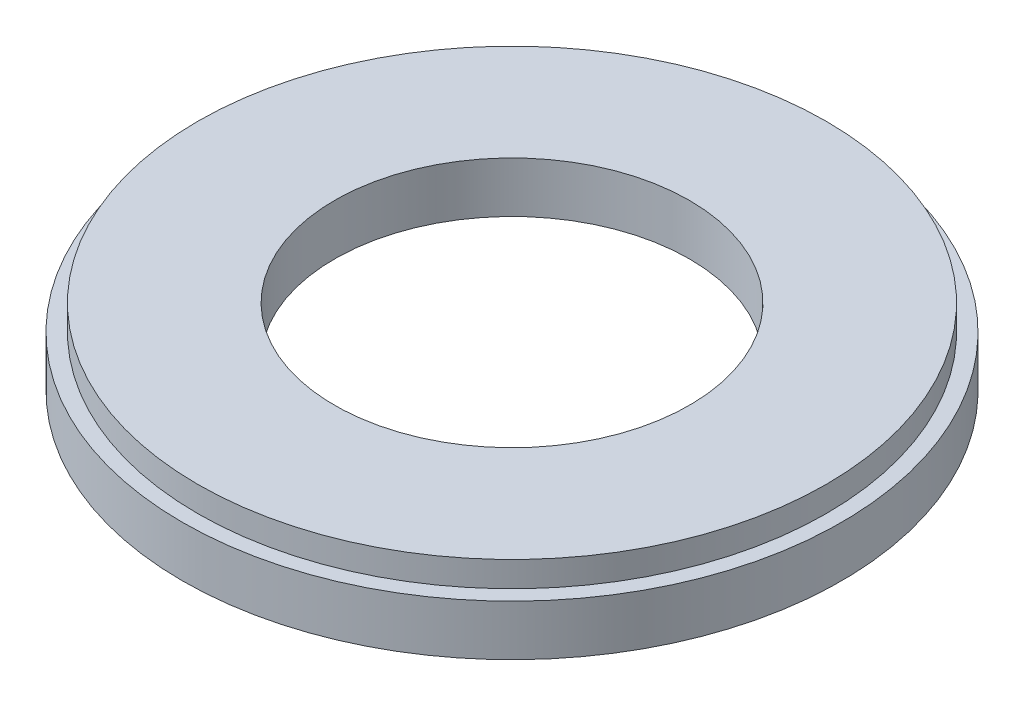
SolidWorks part; units mm, degrees
material "HYPALON"
ref_plane "Front Plane" through (0, 0, 0) normal (0, 0, 1) x (1, 0, 0)
ref_plane "Top Plane" through (0, 0, 0) normal (0, 1, 0) x (1, 0, 0)
ref_plane "Right Plane" through (0, 0, 0) normal (1, 0, 0) x (0, 0, -1)
sketch "Szkic1" plane through (0, 0, 0) normal (0, 0, 1) x (1, 0, 0)
  line L0 (0, 0) -> (-65, 0)
  line L1 (-65, 0) -> (-65, 10)
  line L2 (-65, 10) -> (-35, 10)
  line L3 (-35, 10) -> (-35, 0)
  line L4 (0, 0) -> (0, 23.5461)
  line L6 (-65, 0) -> (-63, 0)
  line L7 (-65, 0) -> (-65, -5)
  line L8 (-65, -5) -> (-63, -5)
  line L9 (-63, 0) -> (-63, -5)
  line L10 (-65, 10) -> (-62, 10)
  line L11 (-65, 10) -> (-65, 5)
  line L12 (-65, 5) -> (-62, 5)
  line L13 (-62, 10) -> (-62, 5)
  dimension "D1" = 65
  dimension "D2" = 10
  dimension "D3" = 35
  dimension "D4" = 3
  dimension "D5" = 5
  dimension "D6" = 5
  dimension "D7" = 2
revolve "Obrót1" add sketch "Szkic1" angle 360 about L4
